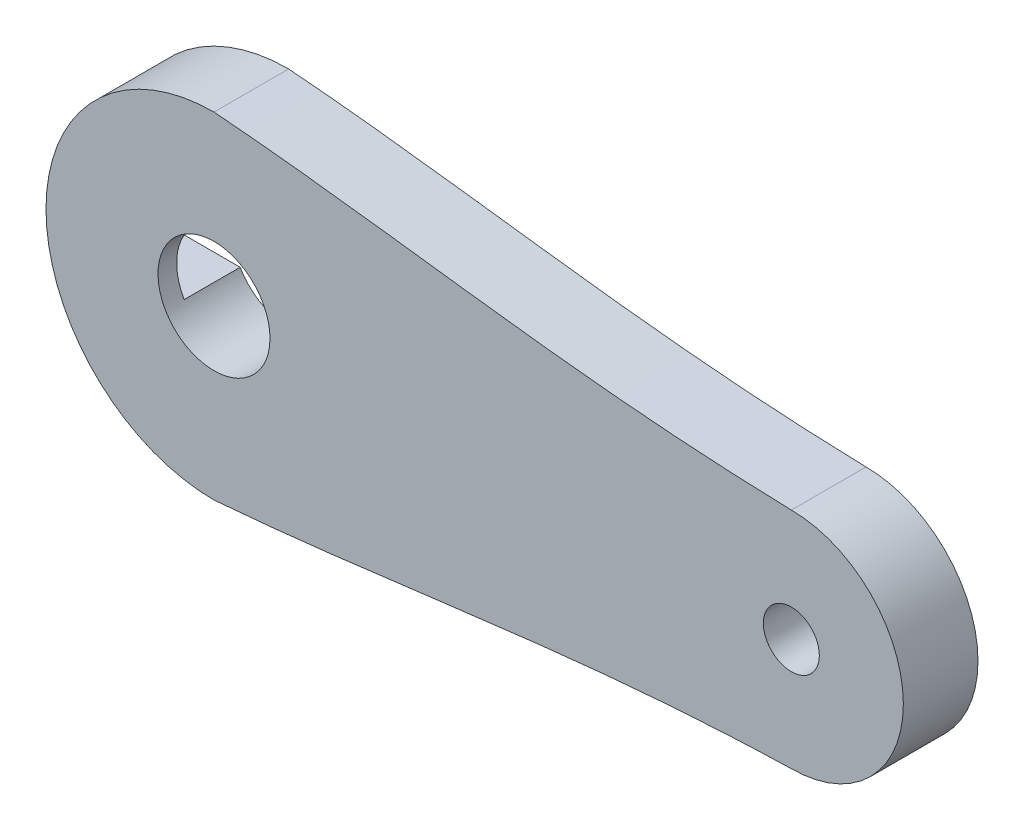
SolidWorks part; units mm, degrees
ref_plane "前视基准面" through (0, 0, 0) normal (0, 0, 1) x (1, 0, 0)
ref_plane "上视基准面" through (0, 0, 0) normal (0, 1, 0) x (1, 0, 0)
ref_plane "右视基准面" through (0, 0, 0) normal (1, 0, 0) x (0, 0, -1)
sketch "草图1" plane through (0, 0, 0) normal (0, 0, 1) x (1, 0, 0)
  line L0 (0, 0) -> (44.3673, 0) construction
  line L1 (-2.5981, 1.5) -> (-7, 1.5) construction
  line L2 (2.5981, -1.5) -> (9, -1.5) construction
  line L3 (9, 1.5) -> (2.5981, 1.5) construction
  line L4 (9, -1.5) -> (9, 1.5) construction
  line L5 (-7, -1.5) -> (-2.5981, -1.5) construction
  line L6 (-7, 0) -> (-7, 1.5) construction
  line L7 (-7, 0) -> (-7, -1.5) construction
  circle A0 centre (0, 0) radius 1.5 construction
  circle A1 centre (0, 0) radius 3
  circle A2 centre (30.93, 0) radius 1.5
  arc A3 (0, 9) -> (0, -9) centre (0, 0) ccw
  arc A4 (30.93, -6) -> (30.93, 6) centre (30.93, 0) ccw
  spline S0 degree 3 poles (0, 9) (10.1126, 8.1884) (18.6899, 6.3282) (30.93, 6) knots 0 0 0 0 1 1 1 1
  spline S1 degree 3 poles (0, -9) (10.1126, -8.1884) (18.6899, -6.3282) (30.93, -6) knots 0 0 0 0 1 1 1 1
  point P0 (0, 0)
  point P3 (30.93, 0)
  point P6 (0, 0)
  point P8 (-7, 0)
  point P9 (9, 0)
  dimension "D1" = 30.93
extrude "凸台-拉伸1" add sketch "草图1" along normal blind 4
sketch "草图2" plane through (0, 0, 0) normal (0, 0, 1) x (1, 0, 0)
  line L0 (-2.5981, 1.5) -> (-7, 1.5) construction
  line L1 (2.5981, -1.5) -> (9, -1.5) construction
  line L2 (9, 1.5) -> (2.5981, 1.5) construction
  line L3 (9, -1.5) -> (9, 1.5) construction
  line L4 (-7, -1.5) -> (-2.5981, -1.5) construction
  line L5 (-7, 0) -> (-7, 1.5) construction
  line L6 (-7, 0) -> (-7, -1.5) construction
  line L7 (-2.5981, 1.5) -> (-7, 1.5)
  line L8 (-7, 1.5) -> (-7, -1.5)
  line L9 (-7, -1.5) -> (9, -1.5)
  line L10 (9, -1.5) -> (9, 1.5)
  line L11 (9, 1.5) -> (-2.5981, 1.5)
  circle A0 centre (0, 0) radius 1.5 construction
  point P1 (0, 0)
  point P3 (-7, 0)
  point P4 (9, 0)
extrude "切除-拉伸1" cut sketch "草图2" along normal blind 3
